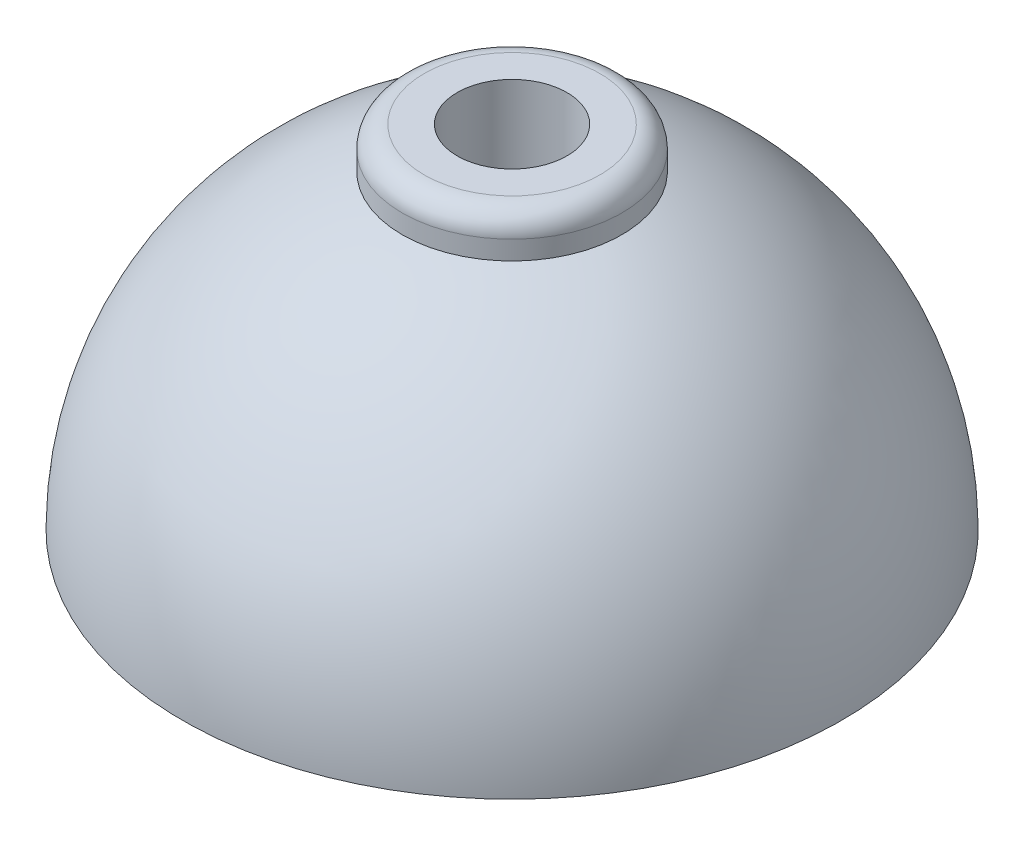
SolidWorks part; units mm, degrees
ref_plane "Front Plane" through (0, 0, 0) normal (0, 0, 1) x (1, 0, 0)
ref_plane "Top Plane" through (0, 0, 0) normal (0, 1, 0) x (1, 0, 0)
ref_plane "Right Plane" through (0, 0, 0) normal (1, 0, 0) x (0, 0, -1)
sketch "Sketch1" plane through (0, 0, 0) normal (0, 0, 1) x (1, 0, 0)
  line L0 (0, 0) -> (0, 18532.3191) construction
  line L1 (0, 0) -> (15, 0)
  line L2 (0, 0) -> (0, 15)
  arc A0 (15, 0) -> (0, 15) centre (0, 0) ccw
  dimension "D1" = 30
revolve "Revolve1" add sketch "Sketch1" angle 360 about L0
shell "Shell1" thickness 2
ref_plane "Plane1" through (0, 15, 0) normal (0, 1, 0) x (1, 0, 0)
sketch "Sketch4" plane through (0, 15, 0) normal (0, 1, 0) x (1, 0, 0)
  circle A0 centre (0, 0) radius 5
  dimension "D1" = 10
extrude "Boss-Extrude6" add sketch "Sketch4" along normal blind 1 and the other way blind 5
sketch "Sketch2" plane through (0, 0, 0) normal (0, 1, 0) x (1, 0, 0)
  circle A0 centre (0, 0) radius 2.5
  dimension "D1" = 5
extrude "Cut-Extrude3" cut sketch "Sketch2" along normal through all
fillet "Fillet1" radius 1 1 edges at (0, 16, 5)
